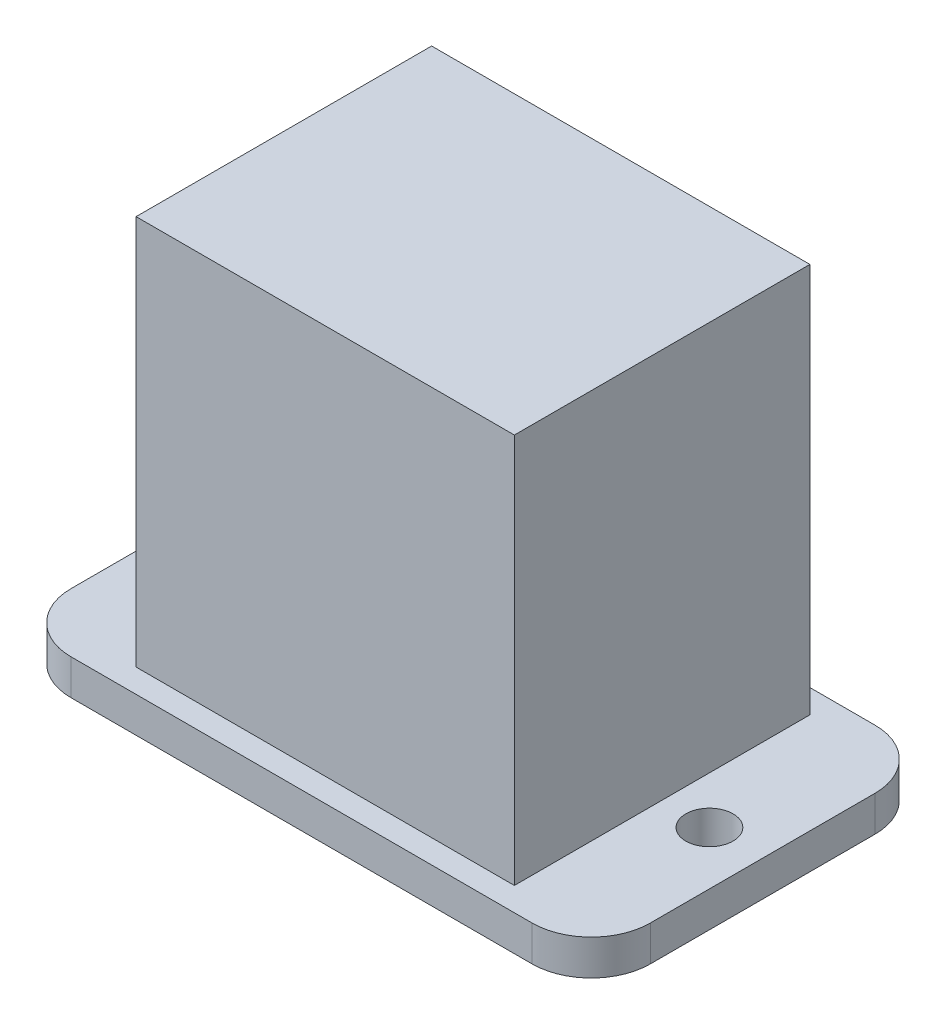
SolidWorks part; units mm, degrees
ref_plane "Front Plane" through (0, 0, 0) normal (0, 0, 1) x (1, 0, 0)
ref_plane "Top Plane" through (0, 0, 0) normal (0, 1, 0) x (1, 0, 0)
ref_plane "Right Plane" through (0, 0, 0) normal (1, 0, 0) x (0, 0, -1)
sketch "Sketch1" plane through (0, 0, 0) normal (0, 1, 0) x (1, 0, 0)
  line L0 (0, 14.5) -> (49, 14.5) construction
  line L1 (5, 0) -> (44, 0)
  line L2 (0, 5) -> (0, 24)
  line L3 (5, 29) -> (44, 29)
  line L4 (49, 5) -> (49, 24)
  arc A0 (0, 24) -> (5, 29) centre (5, 24) cw
  arc A1 (5, 0) -> (0, 5) centre (5, 5) cw
  arc A2 (44, 0) -> (49, 5) centre (44, 5) ccw
  arc A3 (44, 29) -> (49, 24) centre (44, 24) cw
  circle A4 centre (4.5, 14.5) radius 2
  circle A5 centre (44.5, 14.5) radius 2
  point P7 (0, 29)
  point P10 (0, 0)
  point P15 (49, 29)
  dimension "D3" = 5
  dimension "D4" = 4
  dimension "D5" = 4
  dimension "D6" = 40
  dimension "D7" = 4.5
  dimension "D1" = 49
  dimension "D2" = 29
extrude "Boss-Extrude1" add sketch "Sketch1" along normal blind 3
sketch "Sketch2" plane through (0, 3, 0) normal (0, 1, 0) x (1, 0, 0)
  line L0 (0, 5) -> (0, 24) construction
  line L1 (8.5, 27) -> (40.5, 27)
  line L2 (8.5, 27) -> (8.5, 2)
  line L3 (8.5, 2) -> (40.5, 2)
  line L4 (40.5, 27) -> (40.5, 2)
  line L5 (5, 0) -> (44, 0) construction
  dimension "D1" = 32
  dimension "D2" = 25
  dimension "D3" = 8.5
  dimension "D4" = 2
extrude "Boss-Extrude2" add sketch "Sketch2" along normal blind 33
